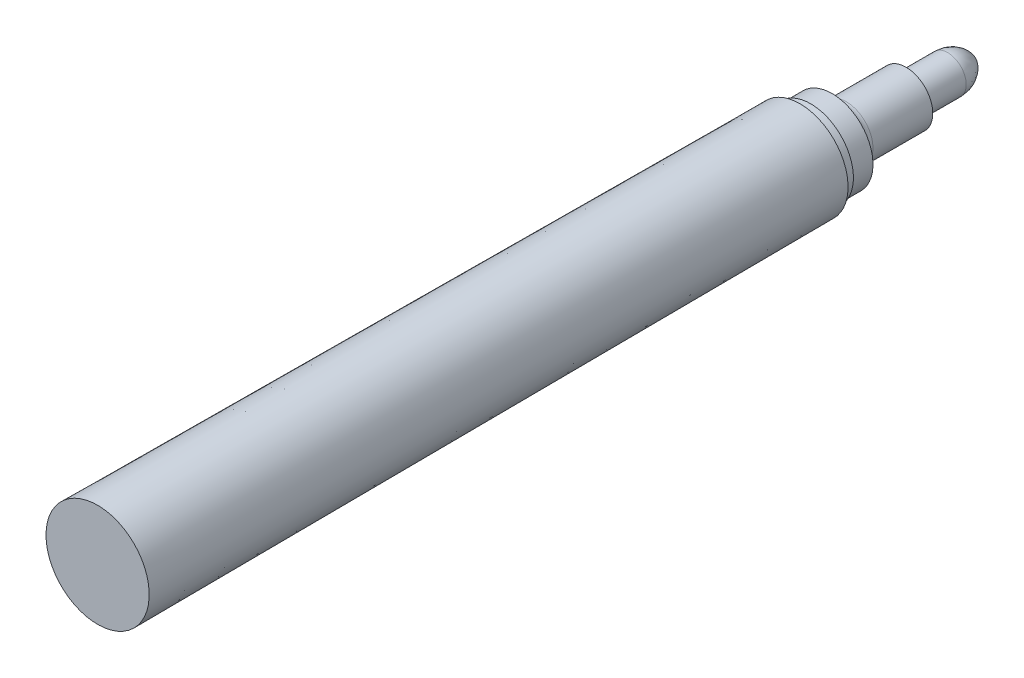
SolidWorks part; units mm, degrees
ref_plane "前视基准面" through (0, 0, 0) normal (0, 0, 1) x (1, 0, 0)
ref_plane "上视基准面" through (0, 0, 0) normal (0, 1, 0) x (1, 0, 0)
ref_plane "右视基准面" through (0, 0, 0) normal (1, 0, 0) x (0, 0, -1)
sketch "草图1" plane through (0, 0, 0) normal (0, 1, 0) x (1, 0, 0)
  line L0 (0, 0) -> (0, -34.2908) construction
  line L1 (0, 0) -> (-7.25, 0)
  line L2 (-7.25, 0) -> (-6.75, 98.6987)
  line L3 (-6.75, 98.6987) -> (0, 98.6987)
  line L4 (0, 98.6987) -> (0, 0)
  dimension "D1" = 14.5
  dimension "D2" = 13.5
  dimension "D3" = 98.7
revolve "旋转1" add sketch "草图1" angle 360 about L0
sketch "草图2" plane through (0, 0, 0) normal (0, 1, 0) x (1, 0, 0)
  line L0 (0, 98.6987) -> (0, 79.609) construction
  line L1 (6.75, 98.6987) -> (-6.75, 98.6987) construction
  line L2 (-6, 98.6987) -> (-6, 100.1987)
  line L3 (-6, 100.1987) -> (-5.75, 100.1987)
  line L4 (-5.75, 100.1987) -> (-5.75, 103.1987)
  line L5 (-3.75, 105.1987) -> (-3.75, 113.5987)
  line L6 (-3.75, 113.5987) -> (-2.6, 113.5987)
  line L7 (-2.6, 113.5987) -> (-2.6, 119.4517)
  line L8 (-6, 98.6987) -> (0, 98.6987)
  line L9 (0, 98.6987) -> (0, 123.1987)
  arc A0 (-3.75, 105.1987) -> (-5.75, 103.1987) centre (-5.75, 105.1987) cw
  arc A1 (-2.6, 119.4517) -> (0, 123.1987) centre (1.4, 119.4517) cw
  dimension "D9" = 4
  dimension "D1" = 24.5
  dimension "D2" = 1.5
  dimension "D3" = 3
  dimension "D4" = 12
  dimension "D5" = 11.5
  dimension "D6" = 7.5
  dimension "D7" = 5.2
  dimension "D8" = 8.4
revolve "旋转2" add sketch "草图2" angle 360 about L0
